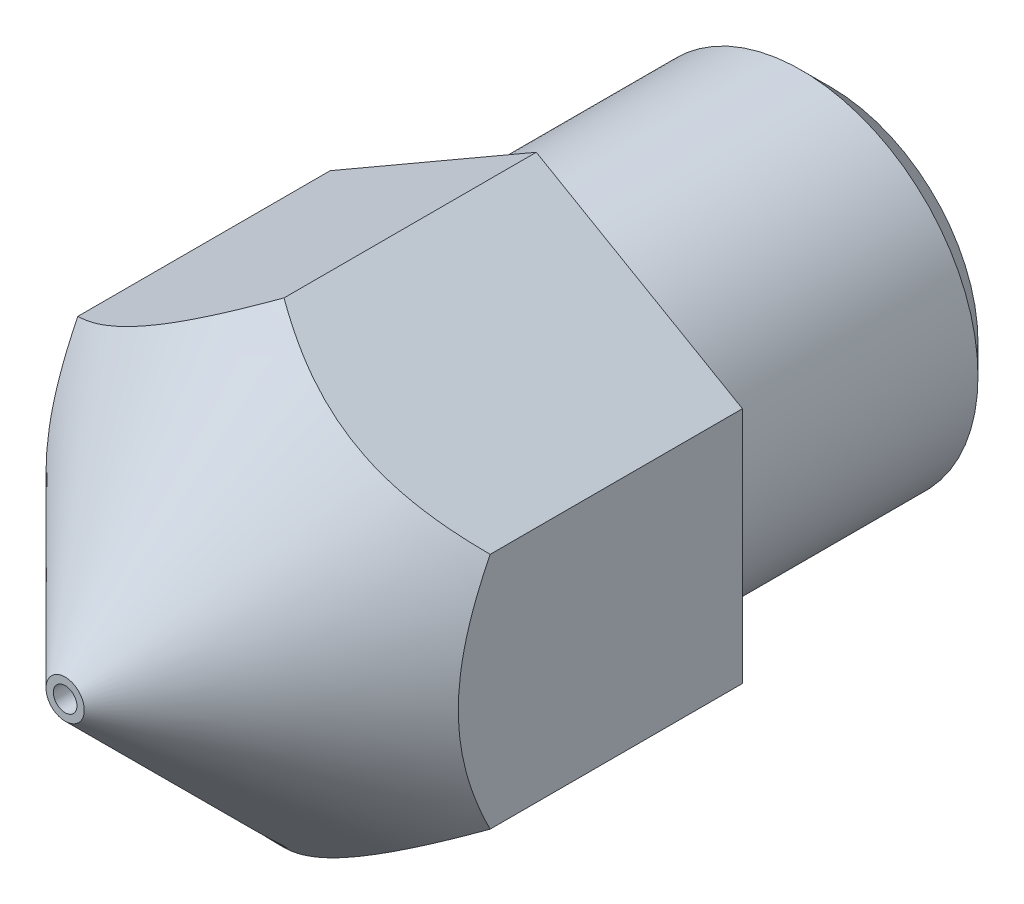
SolidWorks part; units mm, degrees
material "Brass"
ref_plane "Front Plane" through (0, 0, 0) normal (0, 0, 1) x (1, 0, 0)
ref_plane "Top Plane" through (0, 0, 0) normal (0, 1, 0) x (1, 0, 0)
ref_plane "Right Plane" through (0, 0, 0) normal (1, 0, 0) x (0, 0, -1)
sketch "Sketch1" plane through (0, 0, 0) normal (0, 1, 0) x (1, 0, 0)
  line L0 (0, 0) -> (0, -50000) construction
  line L1 (1.19, 0) -> (0, 0) construction
  line L2 (1.19, 0) -> (3, 0)
  line L3 (0.325, -13) -> (8.325, -5)
  line L5 (0.2, -13) -> (0.2, -12.5)
  line L10 (1.19, 0) -> (1.19, -10.7853)
  line L14 (3, 0) -> (3, -5)
  line L20 (0.2, -12.5) -> (1.19, -10.7853)
  line L23 (3, -5) -> (8.325, -5)
  line L24 (0.2, -13) -> (0.325, -13)
  dimension "D2" = 3
  dimension "D3" = 2.38
  dimension "D4" = 0.125
  dimension "D5" = 0.5
  dimension "D6" = 13
  dimension "D7" = 5
  dimension "D8" = 0.4
  dimension "D9" = 45
  dimension "D11" = 30
ref_axis "Axis1" through (0, 0, 0) along (0, 0, 1)
revolve "Revolve1" add sketch "Sketch1" angle 360 about axis through (0, 0, 0) along (0, 0, 1)
sketch "Sketch2" plane through (0, 0, 5) normal (0, 0, -1) x (-1, 0, 0)
  line L0 (0, 0) -> (0, 50000) construction
  line L1 (0, 0) -> (50000, 0) construction
  line L2 (3.5, 2.0207) -> (0, 4.0415)
  line L3 (3.5, 2.0207) -> (3.5, -2.0207)
  line L4 (3.5, -2.0207) -> (0, -4.0415)
  line L5 (0, 0) -> (43301.2702, 25000) construction
  line L6 (0, 0) -> (43062.4912, -24862.1409) construction
  line L7 (-3.5, 2.0207) -> (0, 4.0415)
  line L8 (-3.5, 2.0207) -> (-3.5, -2.0207)
  line L9 (-3.5, -2.0207) -> (0, -4.0415)
  circle A1 centre (0, 0) radius 8.325
  circle A3 centre (0, 0) radius 8.325 construction
  dimension "D1" = 60
  dimension "D2" = 30
  dimension "D3" = 3.5
extrude "Cut-Extrude2" cut sketch "Sketch2" against normal blind 10
chamfer "Chamfer1" distance 0.5 angle 45 1 edges at (-3, 0, 0)
